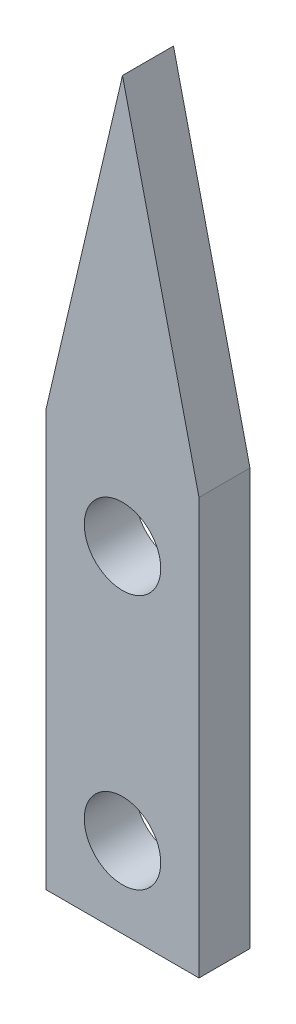
SolidWorks part; units mm, degrees
ref_plane "前视基准面" through (0, 0, 0) normal (0, 0, 1) x (1, 0, 0)
ref_plane "上视基准面" through (0, 0, 0) normal (0, 1, 0) x (1, 0, 0)
ref_plane "右视基准面" through (0, 0, 0) normal (1, 0, 0) x (0, 0, -1)
sketch "草图1" plane through (0, 0, 0) normal (0, 0, 1) x (1, 0, 0)
  line L0 (0, 0) -> (0, -10) construction
  line L1 (0, -10) -> (0, 16) construction
  line L2 (3, 3.1642) -> (0, 16)
  line L3 (3, 3.1642) -> (-3, 3.1642) construction
  line L4 (3, 3.1642) -> (3, -13.1642)
  line L5 (3, -13.1642) -> (-3, -13.1642)
  line L6 (-3, 3.1642) -> (-3, -13.1642)
  line L7 (3, 3.1642) -> (-3, -13.1642) construction
  line L8 (3, -13.1642) -> (-3, 3.1642) construction
  line L9 (0, 16) -> (-3, 3.1642)
  circle A0 centre (0, 0) radius 1.5
  circle A1 centre (0, -10) radius 1.5
  point P7 (0, -5)
extrude "凸台-拉伸1" add sketch "草图1" along normal blind 2
